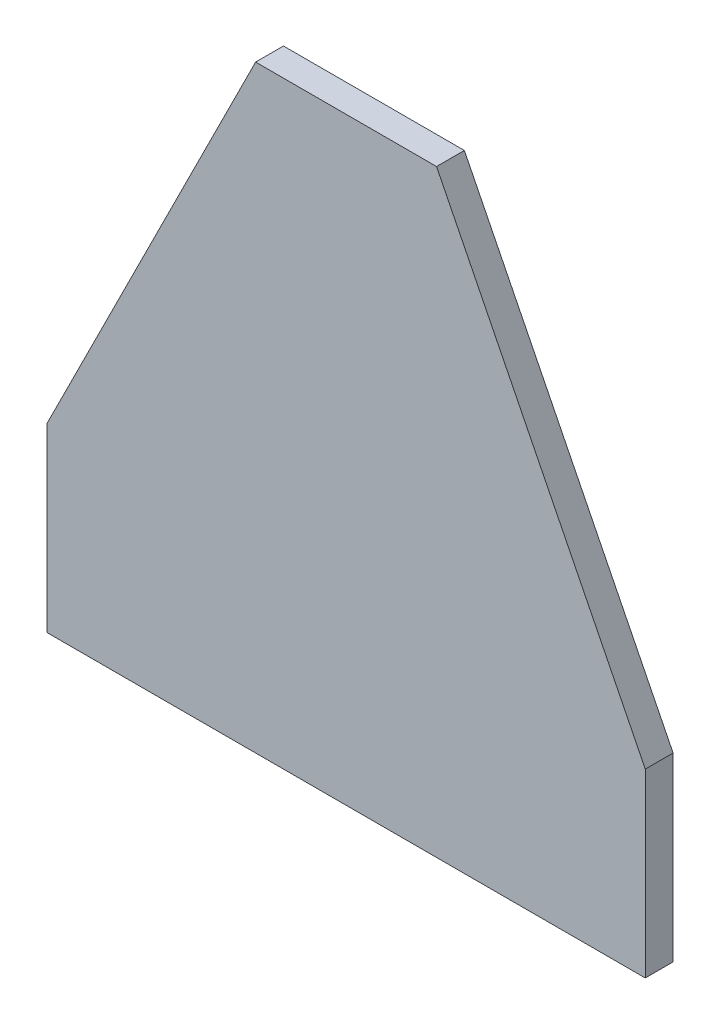
SolidWorks part; units mm, degrees
ref_plane "Front Plane" through (0, 0, 0) normal (0, 0, 1) x (1, 0, 0)
ref_plane "Top Plane" through (0, 0, 0) normal (0, 1, 0) x (1, 0, 0)
ref_plane "Right Plane" through (0, 0, 0) normal (1, 0, 0) x (0, 0, -1)
sketch "Sketch1" plane through (0, 0, 0) normal (0, 0, 1) x (1, 0, 0)
  line L0 (-20.6375, 0) -> (20.6375, 0)
  line L1 (20.6375, 0) -> (68.2625, -95.25)
  line L2 (68.2625, -95.25) -> (68.2625, -136.525)
  line L3 (68.2625, -136.525) -> (-68.2625, -136.525)
  line L4 (-68.2625, -136.525) -> (-68.2625, -95.25)
  line L5 (-68.2625, -95.25) -> (-20.6375, 0)
  line L6 (0, 0) -> (0, -136.525) construction
  line L7 (-68.2625, -115.8875) -> (68.2625, -115.8875) construction
  circle A0 centre (0, -115.8875) radius 7.1437
  circle A1 centre (0, -68.2625) radius 7.1437
  circle A2 centre (0, -20.6375) radius 7.1438
  circle A3 centre (47.625, -115.8875) radius 7.1437
  circle A4 centre (-47.625, -115.8875) radius 7.1437
  circle A5 centre (0, -115.8875) radius 47.625 construction
  dimension "Hole Size" = 14.2875
  dimension "B" = 136.525
  dimension "A" = 136.525
  dimension "D3" = 41.275
  dimension "Spacing" = 47.625
  dimension "D5" = 47.625
extrude "Boss-Extrude1" add sketch "Sketch1" along normal mid plane 6.35
sketch "Sketch2" plane through (0, 0, 3.175) normal (0, 0, 1) x (1, 0, 0)
  circle A0 centre (0, -68.2625) radius 7.1437 construction
  circle A1 centre (0, -68.2625) radius 7.1437
  circle A2 centre (0, -20.6375) radius 7.1438 construction
  circle A3 centre (0, -20.6375) radius 7.1438
  circle A4 centre (-47.625, -115.8875) radius 7.1437 construction
  circle A5 centre (-47.625, -115.8875) radius 7.1437
  circle A6 centre (0, -115.8875) radius 7.1437 construction
  circle A7 centre (0, -115.8875) radius 7.1437
  circle A8 centre (47.625, -115.8875) radius 7.1437 construction
  circle A9 centre (47.625, -115.8875) radius 7.1437
extrude "Boss-Extrude3" add sketch "Sketch2" against normal up to surface (6.35 mm away) up to face at (54.7688, -115.8875, -3.175)
equation "\"D5@Sketch1\" = \"Spacing@Sketch1\""
